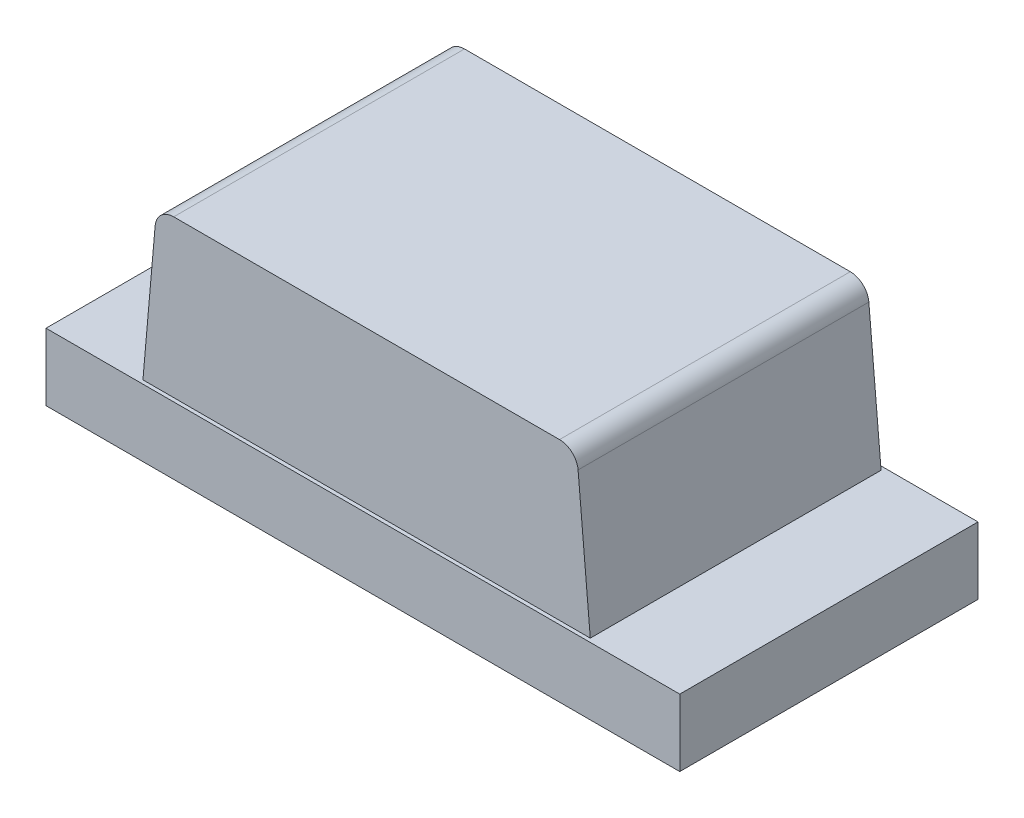
SolidWorks part; units mm, degrees
material "Alloy Steel"
ref_plane "Front Plane" through (0, 0, 0) normal (0, 0, 1) x (1, 0, 0)
ref_plane "Top Plane" through (0, 0, 0) normal (0, 1, 0) x (1, 0, 0)
ref_plane "Right Plane" through (0, 0, 0) normal (1, 0, 0) x (0, 0, -1)
sketch "Sketch1" plane through (0, 0, 0) normal (0, 1, 0) x (1, 0, 0)
  line L1 (0.85, -0.4) -> (-0.85, -0.4)
  line L2 (0.85, -0.4) -> (0.85, 0.4)
  line L3 (0.85, 0.4) -> (-0.85, 0.4)
  line L4 (-0.85, -0.4) -> (-0.85, 0.4)
  line L5 (0.85, -0.4) -> (-0.85, 0.4) construction
  line L6 (0.85, 0.4) -> (-0.85, -0.4) construction
  point P0 (0, 0)
  dimension "D1" = 0.8
  dimension "D2" = 1.7
extrude "Base" add sketch "Sketch1" along normal blind 0.18
sketch "Sketch2" plane through (0, 0, 0) normal (0, 0, 1) x (1, 0, 0)
  line L0 (-0.6, 0.18) -> (-0.5633, 0.6)
  line L1 (-0.85, 0.18) -> (0.85, 0.18) construction
  line L2 (-0.5633, 0.6) -> (0.5633, 0.6)
  line L3 (0.5633, 0.6) -> (0.6, 0.18)
  line L4 (0.6, 0.18) -> (-0.6, 0.18)
  line L5 (0.44, 0) -> (-0.44, 0) construction
  line L6 (0, -0.22) -> (0, 0.22) construction
  point P8 (0, 0.6)
  dimension "D1" = 1.2
  dimension "D2" = 0.6
  dimension "D3" = 10
extrude "Lens" add sketch "Sketch2" along normal offset from surface 0.01 and the other way offset from surface (0.39 mm away) 0.01 up to face at (0, 0.09, 0.4) other way up to face at (0, 0.09, -0.4)
fillet "Lens Rounds" radius 0.05 2 edges at (0.5633, 0.6, 0) (-0.5633, 0.6, 0)
